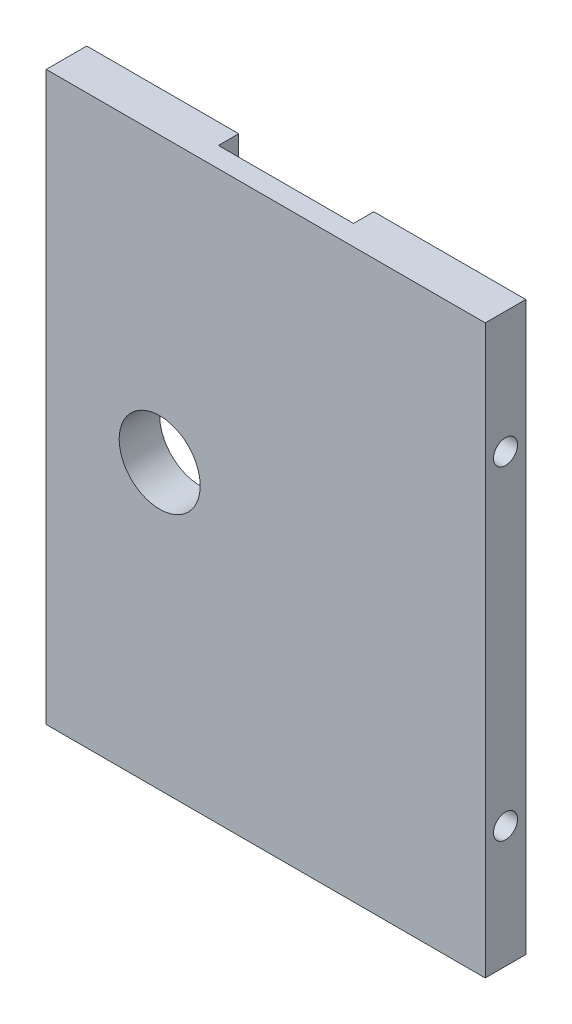
SolidWorks part; units mm, degrees
ref_plane "Front Plane" through (0, 0, 0) normal (0, 0, 1) x (1, 0, 0)
ref_plane "Top Plane" through (0, 0, 0) normal (0, 1, 0) x (1, 0, 0)
ref_plane "Right Plane" through (0, 0, 0) normal (1, 0, 0) x (0, 0, -1)
sketch "Sketch1" plane through (0, 0, 0) normal (0, 0, 1) x (1, 0, 0)
  line L1 (0, 0) -> (32.5, 0)
  line L2 (0, 0) -> (0, 42)
  line L3 (0, 42) -> (32.5, 42)
  line L4 (32.5, 0) -> (32.5, 42)
  point P5 (0, 0)
extrude "Boss-Extrude2" add sketch "Sketch1" along normal blind 3
sketch "Sketch2" plane through (0, 0, 3) normal (0, 0, 1) x (1, 0, 0)
  line L0 (0, 42) -> (0, 33)
  line L1 (0, 42) -> (0, 0) construction
  line L2 (0, 33) -> (32.5, 33)
  line L3 (32.5, 0) -> (32.5, 42) construction
  line L4 (0, 0) -> (0, 9)
  line L5 (0, 9) -> (32.5, 9)
sketch "Sketch3" plane through (0, 0, 0) normal (-1, 0, 0) x (0, 0, 1)
  line L0 (3, 33) -> (0, 33)
  line L1 (3, 42) -> (3, 33) construction
  line L2 (0, 42) -> (0, 0) construction
  line L3 (3, 9) -> (0, 9)
  line L4 (3, 0) -> (3, 9) construction
  line L5 (3, 42) -> (3, 0) construction
hole_wizard "#2-56 Tapped Hole1" positions "Sketch4" profile "Sketch5" tap size "#2-56" standard "ANSI Inch"
sketch "Sketch4" plane through (0, 0, 0) normal (-1, 0, 0) x (0, 0, 1)
  line L0 (3, 33) -> (0, 33) construction
  line L1 (3, 9) -> (0, 9) construction
  point P0 (1.5, 33)
  point P4 (1.5, 9)
sketch "Sketch5" plane through (0, 33, 1.5) normal (0, 1, 0) x (0, 0, 1)
  line L0 (0, 0) -> (0, 5.73)
  line L1 (0, 5.73) -> (0.889, 5.1958)
  line L2 (0.889, 5.1958) -> (0.889, 0)
  line L5 (0.889, 0) -> (0, 0)
  line L10 (0, 5.73) -> (-0.889, 5.1958) construction
  line L11 (0, -6.35) -> (0, 107.95) construction
  dimension "Tap Drill Dia." = 1.778
  dimension "Tap Drill Depth" = 5.73
  dimension "Drill Angle" = 118
cosmetic thread "Hole Thread1" parameters "D1"=4.37, "D2"=2.1844
cosmetic thread "Hole Thread2" parameters "D1"=4.37, "D2"=2.1844
sketch "Sketch6" plane through (32.5, 0, 0) normal (1, 0, 0) x (0, 0, -1)
  line L0 (-3, 33) -> (0, 33)
  line L1 (-3, 9) -> (0, 9)
hole_wizard "#2-56 Tapped Hole2" positions "Sketch7" profile "Sketch8" tap size "#2-56" standard "ANSI Inch"
sketch "Sketch7" plane through (32.5, 0, 0) normal (1, 0, 0) x (0, 0, -1)
  point P0 (-1.5, 33)
  point P3 (-1.5, 9)
sketch "Sketch8" plane through (32.5, 33, 1.5) normal (0, 1, 0) x (0, 0, -1)
  line L0 (0, 0) -> (0, 5.73)
  line L1 (0, 5.73) -> (0.889, 5.1958)
  line L2 (0.889, 5.1958) -> (0.889, 0)
  line L5 (0.889, 0) -> (0, 0)
  line L10 (0, 5.73) -> (-0.889, 5.1958) construction
  line L11 (0, -6.35) -> (0, 107.95) construction
  dimension "Tap Drill Dia." = 1.778
  dimension "Tap Drill Depth" = 5.73
  dimension "Drill Angle" = 118
cosmetic thread "Hole Thread3" parameters "D1"=4.37, "D2"=2.1844
cosmetic thread "Hole Thread4" parameters "D1"=4.37, "D2"=2.1844
sketch "Sketch9" plane through (0, 0, 0) normal (0, 0, -1) x (-1, 0, 0)
  line L0 (0, 21) -> (-32.5, 21)
  line L1 (0, 42) -> (0, 0) construction
  line L2 (-32.5, 0) -> (-32.5, 42) construction
  line L3 (-16.25, 21) -> (-8.4, 21)
  circle A0 centre (-8.4, 21) radius 3
extrude "Cut-Extrude1" cut sketch "Sketch9" against normal blind 3 contours L0 A0 | L0 A0
sketch "Sketch10" plane through (0, 0, 0) normal (0, 0, -1) x (-1, 0, 0)
  line L0 (-32.5, 42) -> (-21.25, 42)
  line L1 (-32.5, 42) -> (0, 42) construction
  line L2 (0, 42) -> (-11.25, 42)
  line L3 (-11.25, 42) -> (-11.25, 35.5)
  line L4 (-11.25, 35.5) -> (-21.25, 35.5)
  line L5 (-21.25, 35.5) -> (-21.25, 42)
  line L7 (-21.25, 42) -> (-11.25, 42)
  line L8 (-21.25, 42) -> (-21.25, 35.5)
  line L9 (-21.25, 35.5) -> (-11.25, 35.5)
  line L10 (-11.25, 42) -> (-11.25, 35.5)
  line M4 (0, 42) -> (-32.5, 42)
extrude "Cut-Extrude2" cut sketch "Sketch10" against normal blind 1.5 contours L5 L4 L3 M4
